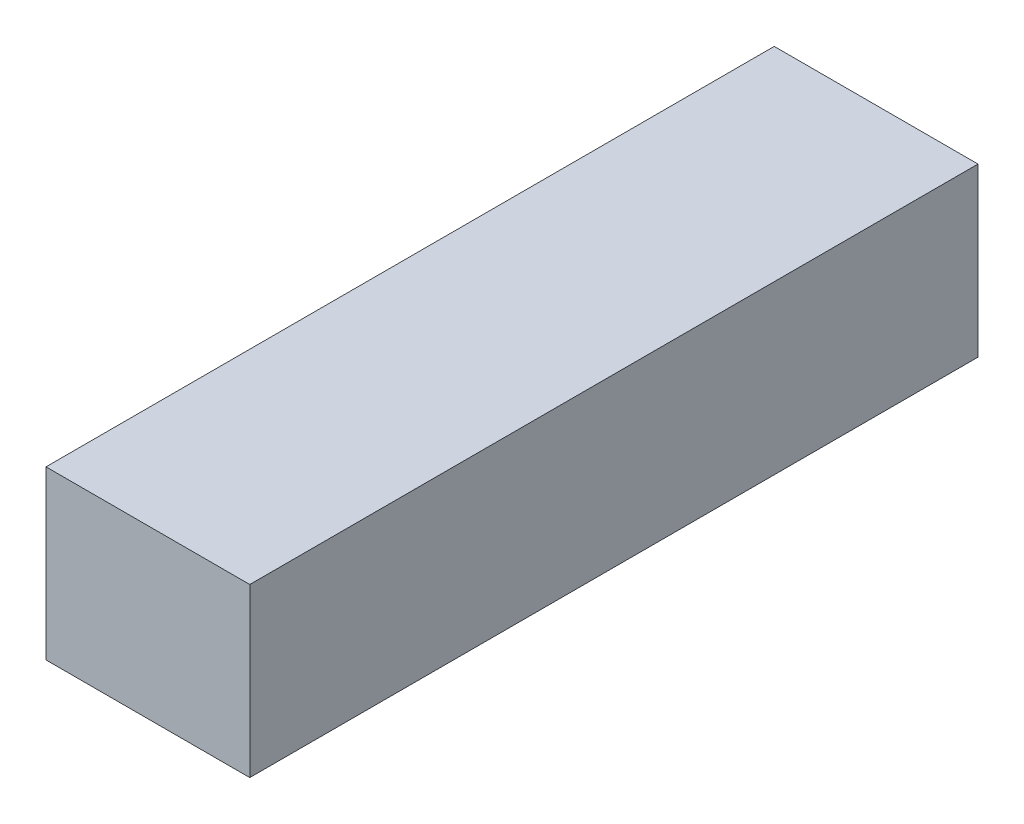
SolidWorks part; units mm, degrees
ref_plane "前视基准面" through (0, 0, 0) normal (0, 0, 1) x (1, 0, 0)
ref_plane "上视基准面" through (0, 0, 0) normal (0, 1, 0) x (1, 0, 0)
ref_plane "右视基准面" through (0, 0, 0) normal (1, 0, 0) x (0, 0, -1)
sketch "草图1" plane through (0, 0, 0) normal (0, 0, 1) x (1, 0, 0)
  line L1 (-69.9524, 57.4146) -> (69.9524, 57.4146)
  line L2 (-69.9524, 57.4146) -> (-69.9524, -57.4146)
  line L3 (-69.9524, -57.4146) -> (69.9524, -57.4146)
  line L4 (69.9524, 57.4146) -> (69.9524, -57.4146)
  line L5 (-69.9524, 57.4146) -> (69.9524, -57.4146) construction
  line L6 (-69.9524, -57.4146) -> (69.9524, 57.4146) construction
  point P0 (0, 0)
extrude "凸台-拉伸1" add sketch "草图1" along normal blind 500
